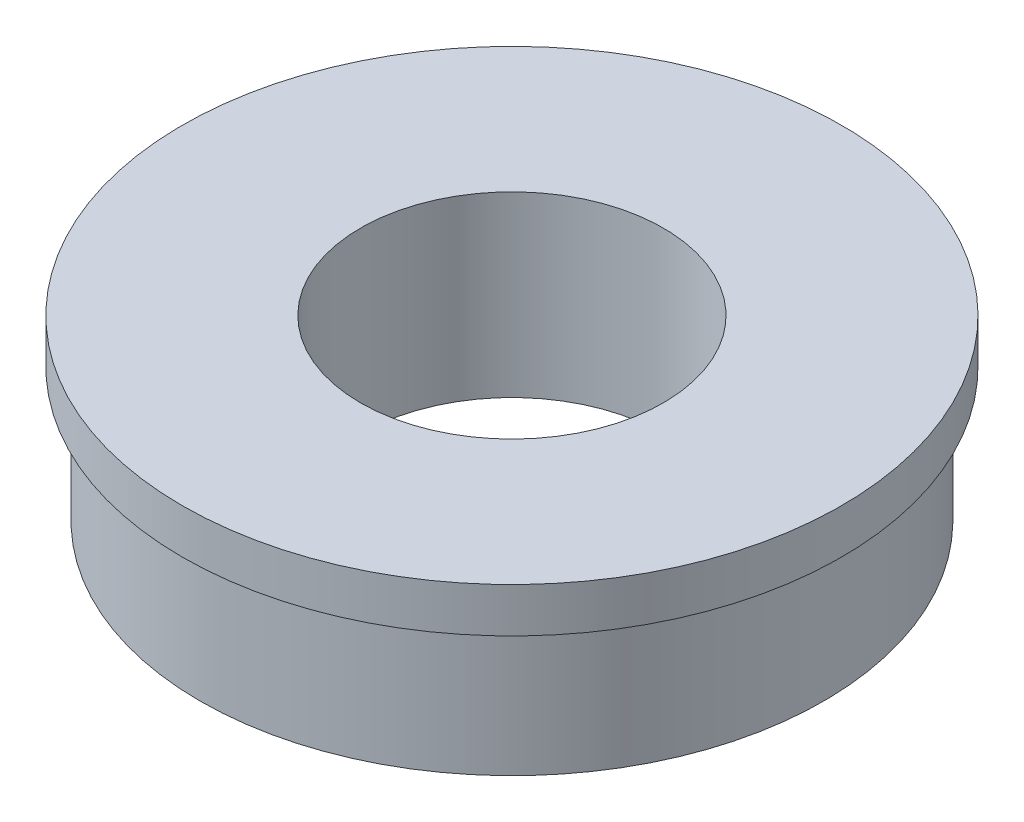
SolidWorks part; units mm, degrees
ref_plane "前视基准面" through (0, 0, 0) normal (0, 0, 1) x (1, 0, 0)
ref_plane "上视基准面" through (0, 0, 0) normal (0, 1, 0) x (1, 0, 0)
ref_plane "右视基准面" through (0, 0, 0) normal (1, 0, 0) x (0, 0, -1)
sketch "Sketch1" plane through (0, 0, 0) normal (0, 0, 1) x (1, 0, 0)
  line L0 (8.5, 0) -> (18.5, 0)
  line L1 (18.5, 0) -> (18.5, -2.5)
  line L2 (18.5, -2.5) -> (17.5, -2.5)
  line L3 (17.5, -2.5) -> (17.5, -10)
  line L4 (17.5, -10) -> (8.5, -10)
  line L5 (8.5, 0) -> (8.5, -10)
  line L6 (0, 8.5649) -> (0, -7.8501) construction
  dimension "D1" = 8.5
  dimension "D2" = 17.5
  dimension "D3" = 10
  dimension "D4" = 18.5
  dimension "D5" = 2.5
revolve "Revolve1" add sketch "Sketch1" angle 360 about L6
